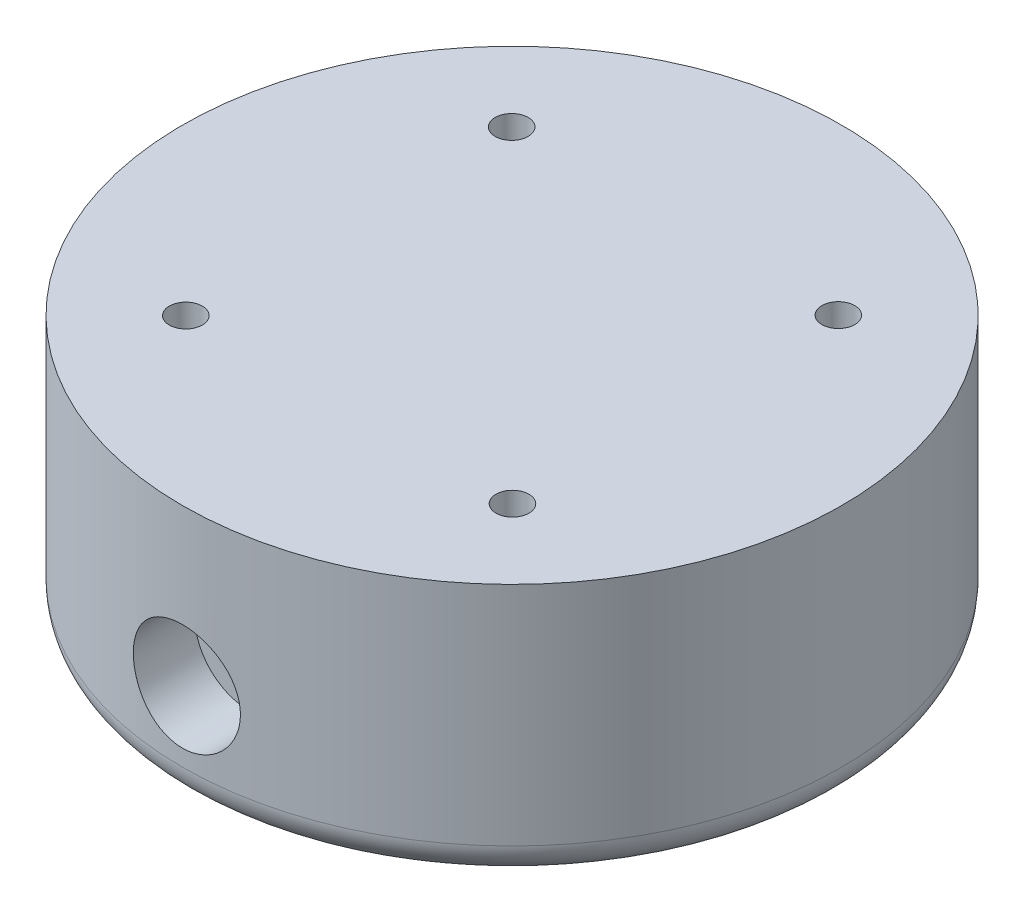
SolidWorks part; units mm, degrees
other "Markup1"
sketch "Sketch3" plane through (-37.5, 0, 37.5) normal (0, 0, 1) x (1, 0, 0)
ref_plane "Front Plane" through (0, 0, 0) normal (0, 0, 1) x (1, 0, 0)
ref_plane "Top Plane" through (0, 0, 0) normal (0, 1, 0) x (1, 0, 0)
ref_plane "Right Plane" through (0, 0, 0) normal (1, 0, 0) x (0, 0, -1)
sketch "Sketch1" plane through (0, 0, 0) normal (0, 1, 0) x (1, 0, 0)
  circle A1 centre (0, 0) radius 40
  dimension "D1" = 80
extrude "Boss-Extrude1" add sketch "Sketch1" along normal blind 31.5
sketch "Sketch2" plane through (0, 0, 0) normal (0, 0, 1) x (1, 0, 0)
  line L0 (-40, 31.5) -> (40, 0) construction
  line L1 (0, 31.5) -> (0, 15.5) construction
  line L2 (40, 31.5) -> (-40, 31.5) construction
  line L3 (-40, 20.5) -> (40, 20.5) construction
  line L5 (-40, 9.5) -> (40, 9.5) construction
  circle A0 centre (0, 12.5) radius 3
  point P6 (0, 15.75)
  point P11 (0, 0)
  point P12 (0, 0)
  point P15 (0, 0)
  dimension "D2" = 6
  dimension "D1" = 16
  dimension "D3" = 5
extrude "Cut-Extrude1" cut sketch "Sketch2" against normal through all both and the other way through all
sketch "Sketch7" plane through (0, 0, 0) normal (0, -1, 0) x (1, 0, 0)
  circle A0 centre (0, 0) radius 10
  circle A1 centre (0, 0) radius 40 construction
  point P2 (0, 0)
  dimension "D1" = 20
extrude "Cut-Extrude3" cut sketch "Sketch7" against normal blind 21
ref_plane "Plane1" through (0, 0, 40) normal (0, 0, 1) x (1, 0, 0)
sketch "Sketch8" plane through (0, 0, 40) normal (0, 0, 1) x (1, 0, 0)
  circle A0 centre (0, 12.5) radius 6.5
  circle A1 centre (0, 12.5) radius 3 construction
  dimension "D1" = 13
extrude "Cut-Extrude4" cut sketch "Sketch8" against normal blind 8
ref_plane "Plane2" through (0, 0, -40) normal (0, 0, -1) x (-1, 0, 0)
sketch "Sketch9" plane through (0, 0, -40) normal (0, 0, -1) x (-1, 0, 0)
  circle A0 centre (0, 12.5) radius 7.5
  circle A1 centre (0, 12.5) radius 3 construction
  dimension "D1" = 15
extrude "Cut-Extrude5" cut sketch "Sketch9" against normal blind 6
sketch "Sketch10" plane through (0, 31.5, 0) normal (0, 1, 0) x (1, 0, 0)
  line L0 (0, 0) -> (0, -40) construction
  line L1 (-21.2132, -21.2132) -> (-28.2843, -28.2843) construction
  line L2 (0, 0) -> (-18.3852, -18.3852) construction
  circle A2 centre (0, 0) radius 40 construction
  circle A3 centre (-19.7745, -19.8239) radius 2
  point P3 (0, 0)
  point P10 (0, 0)
  point P11 (-10.2705, -10.2705)
  point P12 (0, 0)
  point P14 (0, 0)
  point P15 (0, 0)
  point P16 (0, 0)
  dimension "D1" = 45
  dimension "D2" = 3.9994
  dimension "D3" = 4
  dimension "D4" = 10
extrude "Cut-Extrude7" cut sketch "Sketch10" against normal through all both and the other way through all
pattern_circular "CirPattern1" count 4 over 360 about axis through (0, 0, 0) along (0, 1, 0) of "Cut-Extrude7"
ref_plane "Plane3" through (0, 0, 0) normal (0, -1, 0) x (-1, 0, 0)
sketch "Sketch12" plane through (0, 0, 0) normal (0, -1, 0) x (-1, 0, 0)
  circle A0 centre (-19.7745, 19.8239) radius 4
  circle A1 centre (-19.7745, 19.8239) radius 2 construction
  dimension "D1" = 8
extrude "Cut-Extrude8" cut sketch "Sketch12" against normal blind 4
pattern_circular "CirPattern2" count 4 over 360 about axis through (0, 0, 0) along (0, 1, 0) of "Cut-Extrude8"
fillet "Fillet1" radius 4 1 edges at (0, 0, 40)
